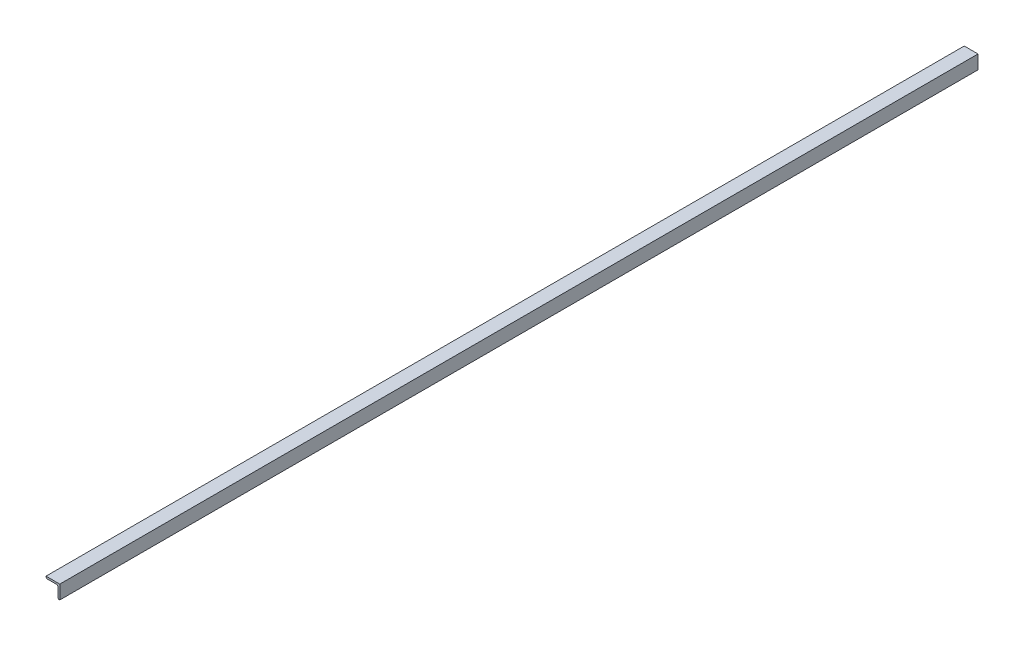
SolidWorks part; units mm, degrees
material "ASTM A36 Steel"
ref_plane "Front Plane" through (0, 0, 0) normal (0, 0, 1) x (1, 0, 0)
ref_plane "Top Plane" through (0, 0, 0) normal (0, 1, 0) x (1, 0, 0)
ref_plane "Right Plane" through (0, 0, 0) normal (1, 0, 0) x (0, 0, -1)
sketch "Sketch1" plane through (0, 0, 0) normal (0, 0, 1) x (1, 0, 0)
  line L0 (-39.6986, 15.8619) -> (-9.6986, 15.8619)
  line L1 (-9.6986, 15.8619) -> (-9.6986, -14.1381)
  line L2 (-9.6986, -14.1381) -> (-10.6986, -14.1381)
  line L3 (-13.6986, -11.1381) -> (-13.6986, 8.8619)
  line L4 (-16.6986, 11.8619) -> (-36.6986, 11.8619)
  line L5 (-39.6986, 14.8619) -> (-39.6986, 15.8619)
  arc A0 (-36.6986, 11.8619) -> (-39.6986, 14.8619) centre (-36.6986, 14.8619) cw
  arc A1 (-13.6986, 8.8619) -> (-16.6986, 11.8619) centre (-16.6986, 8.8619) ccw
  arc A2 (-10.6986, -14.1381) -> (-13.6986, -11.1381) centre (-10.6986, -11.1381) cw
  point P8 (-39.6986, 11.8619)
  point P13 (-13.6986, -14.1381)
  dimension "D5" = 3
  dimension "D1" = 30
  dimension "D2" = 30
  dimension "D3" = 4
  dimension "D4" = 4
extrude "Boss-Extrude1" add sketch "Sketch1" along normal blind 2000
